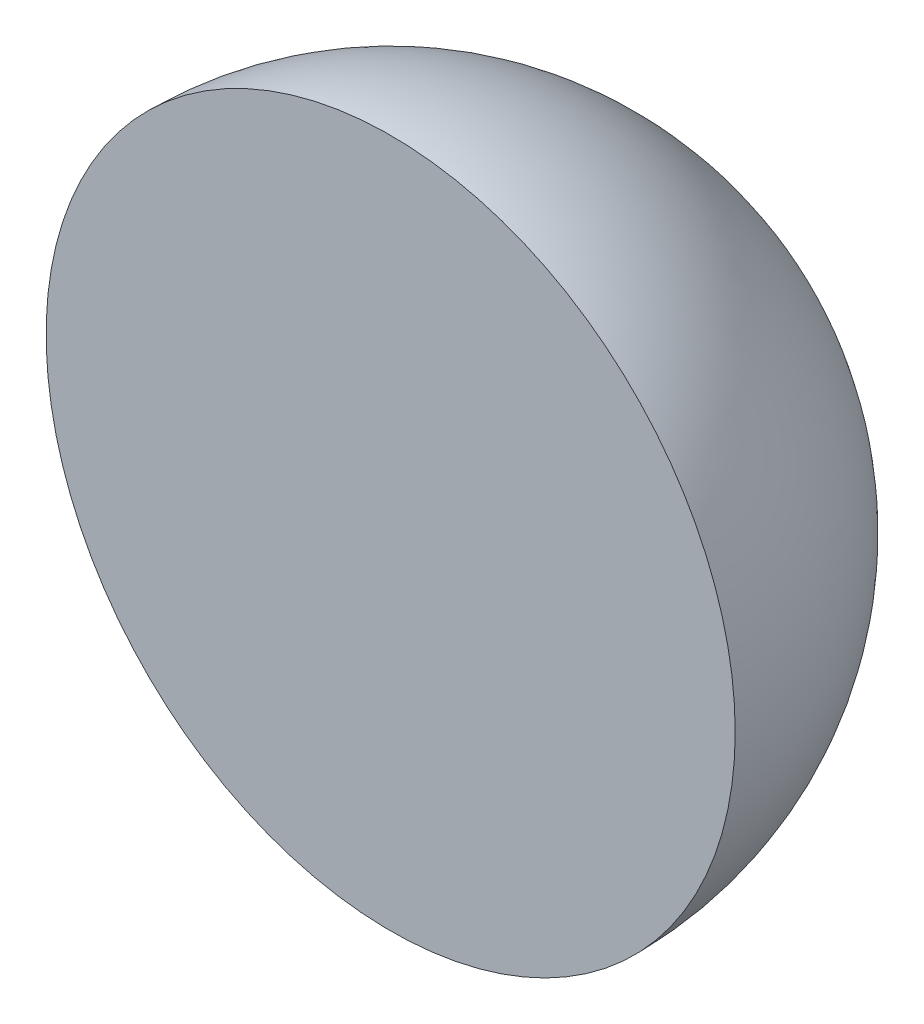
SolidWorks part; units mm, degrees
material "Glass"
ref_plane "Front Plane" through (0, 0, 0) normal (0, 0, 1) x (1, 0, 0)
ref_plane "Top Plane" through (0, 0, 0) normal (0, 1, 0) x (1, 0, 0)
ref_plane "Right Plane" through (0, 0, 0) normal (1, 0, 0) x (0, 0, -1)
ref_plane "Plane1" through (0, 0, 1.5) normal (0, 0, 1) x (1, 0, 0)
sketch "Sketch1" plane through (0, 0, 1.5) normal (0, 0, 1) x (1, 0, 0)
  line L0 (0, 1.5) -> (0, -1.5)
  line L1 (0, 1.5) -> (0, -1.5846) construction
  arc A0 (1.5, 0) -> (0, 1.5) centre (0, 0) ccw
  arc A1 (1.5, 0) -> (0, -1.5) centre (0, 0) cw
revolve "Revolve1" add sketch "Sketch1" angle 180 about L1
